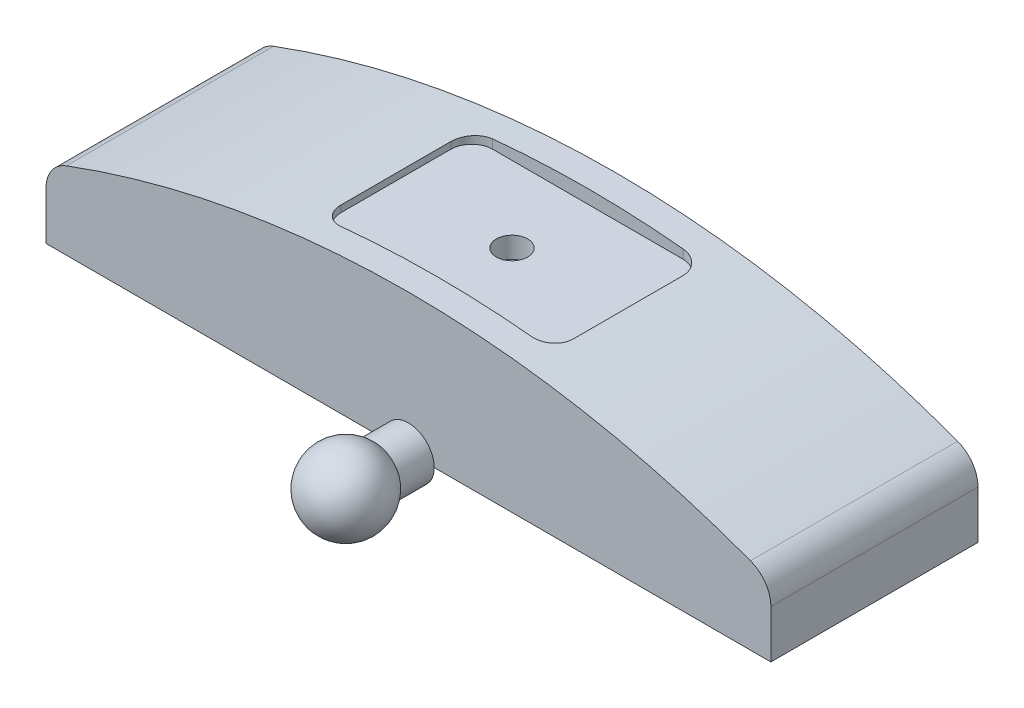
SolidWorks part; units mm, degrees
ref_plane "Front Plane" through (0, 0, 0) normal (0, 0, 1) x (1, 0, 0)
ref_plane "Top Plane" through (0, 0, 0) normal (0, 1, 0) x (1, 0, 0)
ref_plane "Right Plane" through (0, 0, 0) normal (1, 0, 0) x (0, 0, -1)
sketch "Sketch1" plane through (0, 0, 0) normal (0, 1, 0) x (1, 0, 0)
  line L1 (-34.65, -9.9) -> (34.65, -9.9)
  line L2 (-34.65, -9.9) -> (-34.65, 9.9)
  line L3 (-34.65, 9.9) -> (34.65, 9.9)
  line L4 (34.65, -9.9) -> (34.65, 9.9)
  line L5 (-34.65, -9.9) -> (34.65, 9.9) construction
  line L6 (-34.65, 9.9) -> (34.65, -9.9) construction
  point P0 (0, 0)
  dimension "D1" = 69.3
  dimension "D2" = 19.8
extrude "Boss-Extrude1" add sketch "Sketch1" along normal blind 13.3
sketch "Sketch2" plane through (0, 0, 0) normal (0, 1, 0) x (1, 0, 0)
  line L0 (0, 0) -> (0, -15.8927) construction
  line L1 (2.465, -9.9) -> (2.465, -13.12)
  line L2 (-34.65, -9.9) -> (34.65, -9.9) construction
  line L3 (0, -15.8927) -> (0, -22.8367) construction
  line L4 (2.465, -9.9) -> (0, -9.9)
  line L5 (0, -9.9) -> (0, -19.6027)
  arc A0 (0, -19.6027) -> (2.465, -13.12) centre (0, -15.8927) ccw
  dimension "D1" = 7.42
  dimension "D2" = 4.93
  dimension "D3" = 3.22
revolve "Revolve1" add sketch "Sketch2" angle 360 about L0
sketch "Sketch3" plane through (0, 0, -9.9) normal (0, 0, -1) x (-1, 0, 0)
  line L0 (-34.65, 13.3) -> (-34.65, 0) construction
  line L1 (34.65, 13.3) -> (34.65, 0) construction
  line L6 (-34.65, 0) -> (34.65, 0)
  line L7 (34.65, 0) -> (34.65, 13.3)
  line L8 (34.65, 13.3) -> (-34.65, 13.3)
  line L9 (-34.65, 13.3) -> (-34.65, 0)
  line L11 (34.65, 6.65) -> (34.65, 13.3)
  line L12 (34.65, 13.3) -> (-34.65, 13.3)
  line L13 (-34.65, 13.3) -> (-34.65, 6.65)
  arc A0 (-34.65, 6.65) -> (34.65, 6.65) centre (0, -80.2974) cw
  line M6 (34.65, 0) -> (34.65, 13.3)
  line M7 (34.65, 13.3) -> (-34.65, 13.3)
  line M8 (-34.65, 13.3) -> (-34.65, 0)
  dimension "D1" = 0
extrude "Cut-Extrude1" cut sketch "Sketch3" against normal through all contours A0 L12 M8 | A0 M7 M6
ref_plane "Plane1" through (0, 15, 0) normal (0, 1, 0) x (1, 0, 0)
sketch "Sketch4" plane through (0, 15, 0) normal (0, 1, 0) x (1, 0, 0)
  line L1 (-9.1, -7.25) -> (9.1, -7.25)
  line L2 (-11.1, -5.25) -> (-11.1, 5.25)
  line L3 (-9.1, 7.25) -> (9.1, 7.25)
  line L4 (11.1, -5.25) -> (11.1, 5.25)
  line L5 (-11.1, -7.25) -> (11.1, 7.25) construction
  line L6 (-11.1, 7.25) -> (11.1, -7.25) construction
  arc A0 (9.1, 7.25) -> (11.1, 5.25) centre (9.1, 5.25) cw
  arc A1 (9.1, -7.25) -> (11.1, -5.25) centre (9.1, -5.25) ccw
  arc A2 (-9.1, -7.25) -> (-11.1, -5.25) centre (-9.1, -5.25) cw
  arc A3 (-11.1, 5.25) -> (-9.1, 7.25) centre (-9.1, 5.25) cw
  point P0 (0, 0)
  dimension "D3" = 2
  dimension "D1" = 22.2
  dimension "D2" = 14.5
extrude "Cut-Extrude2" cut sketch "Sketch4" against normal blind 3
sketch "Sketch5" plane through (0, 12, 0) normal (0, 1, 0) x (1, 0, 0)
  circle A0 centre (0, 0) radius 1.5
  dimension "D1" = 3
extrude "Cut-Extrude3" cut sketch "Sketch5" against normal blind 2
fillet "Fillet1" radius 3 2 edges at (34.65, 6.65, 0) (-34.65, 6.65, 0)
